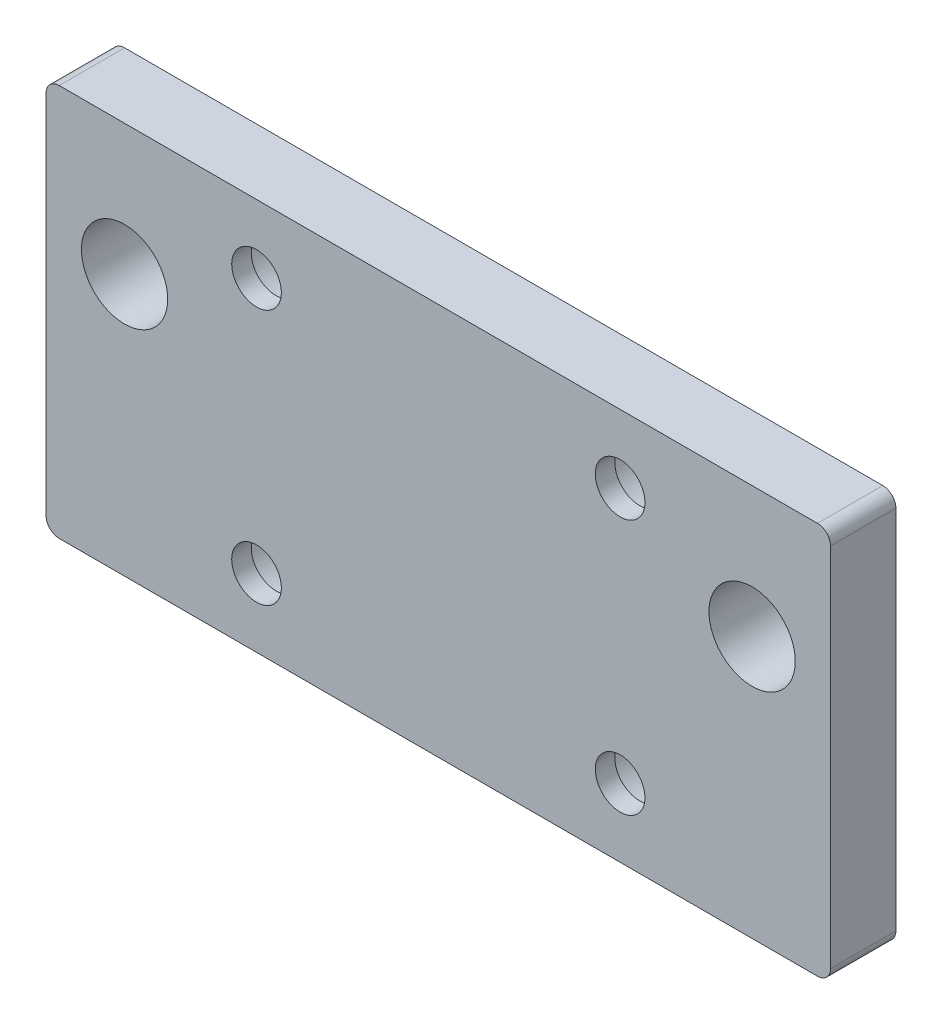
SolidWorks part; units mm, degrees
material "ABS"
ref_plane "Front Plane" through (0, 0, 0) normal (0, 0, 1) x (1, 0, 0)
ref_plane "Top Plane" through (0, 0, 0) normal (0, 1, 0) x (1, 0, 0)
ref_plane "Right Plane" through (0, 0, 0) normal (1, 0, 0) x (0, 0, -1)
sketch "Sketch1" plane through (0, 0, 0) normal (0, 0, 1) x (1, 0, 0)
  line L1 (0, 0) -> (60, 0)
  line L2 (0, 0) -> (0, 30)
  line L3 (0, 30) -> (60, 30)
  line L4 (60, 0) -> (60, 30)
  dimension "D1" = 30
  dimension "D2" = 60
extrude "Boss-Extrude1" add sketch "Sketch1" along normal blind 5
hole_wizard "M6 Clearance Hole1" positions "Sketch2" profile "Sketch4" hole size "M6" standard "ANSI Metric" end condition up to next
sketch "Sketch2" plane through (0, 0, 5) normal (0, 0, 1) x (1, 0, 0)
  line L0 (0, 30) -> (0, 0) construction
  line L1 (60, 0) -> (60, 30) construction
  line L2 (60, 30) -> (0, 30) construction
  point P0 (6, 20)
  point P2 (54, 20)
  dimension "D1" = 6
  dimension "D2" = 6
  dimension "D3" = 10
sketch "Sketch4" plane through (6, 20, 5) normal (1, 0, 0) x (0, -1, 0)
  line L0 (0, 0) -> (0, 5)
  line L1 (0, 5) -> (3.3, 5)
  line L2 (3.3, 5) -> (3.3, 0)
  line L5 (3.3, 0) -> (0, 0)
  line L11 (0, -6.35) -> (0, 107.95) construction
  dimension "Thru Hole Dia." = 6.6
  dimension "Thru Hole Depth" = 5
fillet "Fillet1" radius 1 4 edges at (60, 30, 2.5) (60, 0, 2.5) (0, 0, 2.5) (0, 30, 2.5)
hole_wizard "CBORE for #6 Socket Head Cap Screw1" positions "Sketch7" profile "Sketch8" counterbore size "#6" standard "ANSI Inch" end condition up to next
sketch "Sketch7" plane through (0, 0, 0) normal (0, 0, -1) x (-1, 0, 0)
  point P0 (-43.9055, 24.779)
  point P3 (-16.0945, 24.779)
  point P6 (-43.9055, 5.221)
  point P9 (-16.0945, 5.221)
sketch "Sketch8" plane through (43.9055, 24.779, 0) normal (1, 0, 0) x (0, 1, 0)
  line L0 (0, 0) -> (0, 5)
  line L1 (0, 5) -> (1.8986, 5)
  line L3 (1.8986, 5) -> (1.8986, 3.5052)
  line L4 (1.8986, 3.5052) -> (3.5725, 3.5052)
  line L5 (3.5725, 3.5052) -> (3.5725, 0)
  line L7 (3.5725, 0) -> (0, 0)
  line L11 (0, -6.35) -> (0, 107.95) construction
  dimension "Thru Hole Dia." = 3.7973
  dimension "Thru Hole Depth" = 5
  dimension "C'Bore Dia." = 7.145
  dimension "C'Bore Depth" = 3.5052
